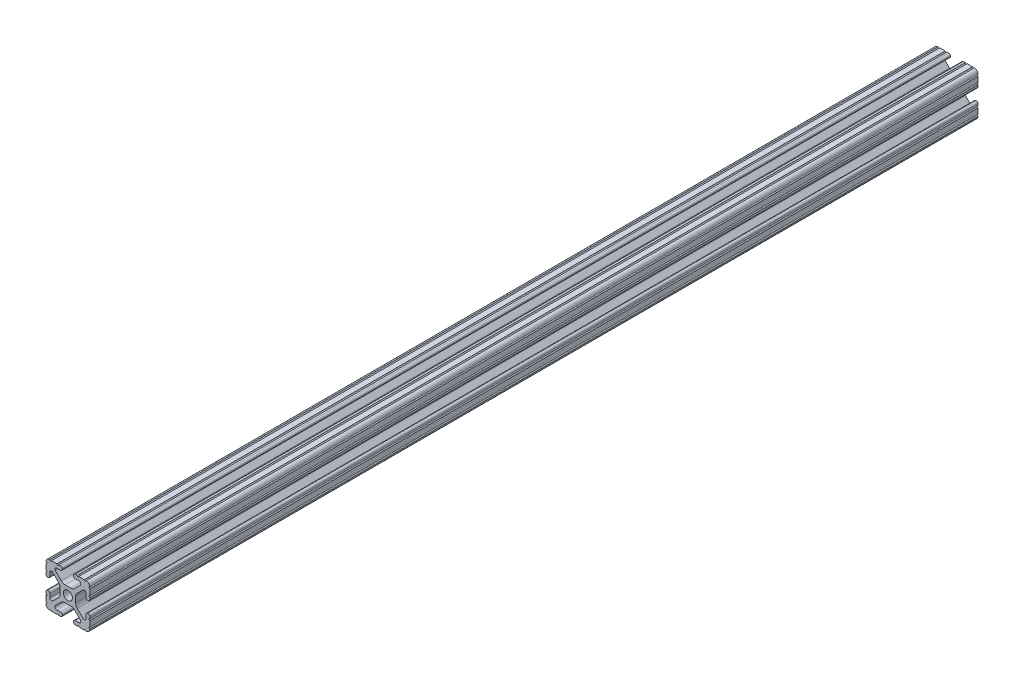
SolidWorks part; units mm, degrees
ref_plane "Front Plane" through (0, 0, 0) normal (0, 0, 1) x (1, 0, 0)
ref_plane "Top Plane" through (0, 0, 0) normal (0, 1, 0) x (1, 0, 0)
ref_plane "Right Plane" through (0, 0, 0) normal (1, 0, 0) x (0, 0, -1)
sketch "Sketch1" plane through (0, 0, 0) normal (0, 0, 1) x (1, 0, 0)
  line L88 (-7.1797, -8.6452) -> (-3.9523, -5.4237)
  line L89 (-1.7093, -4.4958) -> (1.7093, -4.4958)
  line L90 (3.9523, -5.4237) -> (7.1797, -8.6452)
  line L91 (6.4164, -10.4902) -> (4.2875, -10.4902)
  line L92 (3.2385, -11.5392) -> (3.2385, -11.651)
  line L93 (4.2875, -12.7) -> (5.3171, -12.7)
  line L94 (6.3331, -12.7) -> (9.5504, -12.7)
  line L95 (12.7, -9.5504) -> (12.7, -6.3331)
  line L96 (12.7, -5.3171) -> (12.7, -4.2875)
  line L97 (11.651, -3.2385) -> (11.5392, -3.2385)
  line L98 (10.4902, -4.2875) -> (10.4902, -6.4021)
  line L99 (8.7371, -7.1294) -> (5.441, -3.8408)
  line L100 (4.5085, -1.5932) -> (4.5085, 1.5932)
  line L101 (5.441, 3.8408) -> (8.7371, 7.1294)
  line L102 (10.4902, 6.4021) -> (10.4902, 4.2875)
  line L103 (11.5392, 3.2385) -> (11.651, 3.2385)
  line L104 (12.7, 4.2875) -> (12.7, 5.3171)
  line L105 (12.7, 6.3331) -> (12.7, 9.5504)
  line L106 (9.5504, 12.7) -> (6.3331, 12.7)
  line L107 (5.3171, 12.7) -> (4.2875, 12.7)
  line L108 (3.2385, 11.651) -> (3.2385, 11.5392)
  line L109 (4.2875, 10.4902) -> (6.4768, 10.4902)
  line L110 (7.207, 8.7244) -> (3.8983, 5.4232)
  line L111 (1.6558, 4.4958) -> (-1.6558, 4.4958)
  line L112 (-3.8983, 5.4232) -> (-7.207, 8.7244)
  line L113 (-6.4768, 10.4902) -> (-4.2875, 10.4902)
  line L114 (-3.2385, 11.5392) -> (-3.2385, 11.651)
  line L115 (-4.2875, 12.7) -> (-5.3171, 12.7)
  line L116 (-6.3331, 12.7) -> (-9.5504, 12.7)
  line L117 (-12.7, 9.5504) -> (-12.7, 6.3331)
  line L118 (-12.7, 5.3171) -> (-12.7, 4.2875)
  line L119 (-11.651, 3.2385) -> (-11.5392, 3.2385)
  line L120 (-10.4902, 4.2875) -> (-10.4902, 6.4021)
  line L121 (-8.7371, 7.1294) -> (-5.441, 3.8408)
  line L122 (-4.5085, 1.5932) -> (-4.5085, -1.5932)
  line L123 (-5.441, -3.8408) -> (-8.7371, -7.1294)
  line L124 (-10.4902, -6.4021) -> (-10.4902, -4.2875)
  line L125 (-11.5392, -3.2385) -> (-11.651, -3.2385)
  line L126 (-12.7, -4.2875) -> (-12.7, -5.3171)
  line L127 (-12.7, -6.3331) -> (-12.7, -9.5504)
  line L128 (-9.5504, -12.7) -> (-6.3331, -12.7)
  line L129 (-5.3171, -12.7) -> (-4.2875, -12.7)
  line L130 (-3.2385, -11.651) -> (-3.2385, -11.5392)
  line L131 (-4.2875, -10.4902) -> (-6.4164, -10.4902)
  circle A1 centre (0, 0) radius 2.6035
  arc A104 (-7.1797, -8.6452) -> (-6.4164, -10.4902) centre (-6.4164, -9.4098) ccw
  arc A105 (-1.7093, -4.4958) -> (-3.9523, -5.4237) centre (-1.7093, -7.6708) ccw
  arc A106 (3.9523, -5.4237) -> (1.7093, -4.4958) centre (1.7093, -7.6708) ccw
  arc A107 (6.4164, -10.4902) -> (7.1797, -8.6452) centre (6.4164, -9.4098) ccw
  arc A108 (4.2875, -10.4902) -> (3.2385, -11.5392) centre (4.2875, -11.5392) ccw
  arc A109 (3.2385, -11.651) -> (4.2875, -12.7) centre (4.2875, -11.651) ccw
  arc A110 (6.3331, -12.7) -> (5.3171, -12.7) centre (5.8251, -12.7) ccw
  arc A111 (10.5664, -12.6998) -> (9.5504, -12.7) centre (10.0584, -12.7) ccw
  arc A112 (10.5664, -12.6998) -> (12.6998, -10.5664) centre (10.5918, -10.5918) ccw
  arc A113 (12.7, -9.5504) -> (12.6998, -10.5664) centre (12.7, -10.0584) ccw
  arc A114 (12.7, -5.3171) -> (12.7, -6.3331) centre (12.7, -5.8251) ccw
  arc A115 (12.7, -4.2875) -> (11.651, -3.2385) centre (11.651, -4.2875) ccw
  arc A116 (11.5392, -3.2385) -> (10.4902, -4.2875) centre (11.5392, -4.2875) ccw
  arc A117 (8.7371, -7.1294) -> (10.4902, -6.4021) centre (9.4628, -6.4021) ccw
  arc A118 (4.5085, -1.5932) -> (5.441, -3.8408) centre (7.6835, -1.5932) ccw
  arc A119 (5.441, 3.8408) -> (4.5085, 1.5932) centre (7.6835, 1.5932) ccw
  arc A120 (10.4902, 6.4021) -> (8.7371, 7.1294) centre (9.4628, 6.4021) ccw
  arc A121 (10.4902, 4.2875) -> (11.5392, 3.2385) centre (11.5392, 4.2875) ccw
  arc A122 (11.651, 3.2385) -> (12.7, 4.2875) centre (11.651, 4.2875) ccw
  arc A123 (12.7, 6.3331) -> (12.7, 5.3171) centre (12.7, 5.8251) ccw
  arc A124 (12.6998, 10.5664) -> (12.7, 9.5504) centre (12.7, 10.0584) ccw
  arc A125 (12.6998, 10.5664) -> (10.5664, 12.6998) centre (10.5918, 10.5918) ccw
  arc A126 (9.5504, 12.7) -> (10.5664, 12.6998) centre (10.0584, 12.7) ccw
  arc A127 (5.3171, 12.7) -> (6.3331, 12.7) centre (5.8251, 12.7) ccw
  arc A128 (4.2875, 12.7) -> (3.2385, 11.651) centre (4.2875, 11.651) ccw
  arc A129 (3.2385, 11.5392) -> (4.2875, 10.4902) centre (4.2875, 11.5392) ccw
  arc A130 (7.207, 8.7244) -> (6.4768, 10.4902) centre (6.4768, 9.4563) ccw
  arc A131 (1.6558, 4.4958) -> (3.8983, 5.4232) centre (1.6558, 7.6708) ccw
  arc A132 (-3.8983, 5.4232) -> (-1.6558, 4.4958) centre (-1.6558, 7.6708) ccw
  arc A133 (-6.4768, 10.4902) -> (-7.207, 8.7244) centre (-6.4768, 9.4563) ccw
  arc A134 (-4.2875, 10.4902) -> (-3.2385, 11.5392) centre (-4.2875, 11.5392) ccw
  arc A135 (-3.2385, 11.651) -> (-4.2875, 12.7) centre (-4.2875, 11.651) ccw
  arc A136 (-6.3331, 12.7) -> (-5.3171, 12.7) centre (-5.8251, 12.7) ccw
  arc A137 (-10.5664, 12.6998) -> (-9.5504, 12.7) centre (-10.0584, 12.7) ccw
  arc A138 (-10.5664, 12.6998) -> (-12.6998, 10.5664) centre (-10.5918, 10.5918) ccw
  arc A139 (-12.7, 9.5504) -> (-12.6998, 10.5664) centre (-12.7, 10.0584) ccw
  arc A140 (-12.7, 5.3171) -> (-12.7, 6.3331) centre (-12.7, 5.8251) ccw
  arc A141 (-12.7, 4.2875) -> (-11.651, 3.2385) centre (-11.651, 4.2875) ccw
  arc A142 (-11.5392, 3.2385) -> (-10.4902, 4.2875) centre (-11.5392, 4.2875) ccw
  arc A143 (-8.7371, 7.1294) -> (-10.4902, 6.4021) centre (-9.4628, 6.4021) ccw
  arc A144 (-4.5085, 1.5932) -> (-5.441, 3.8408) centre (-7.6835, 1.5932) ccw
  arc A145 (-5.441, -3.8408) -> (-4.5085, -1.5932) centre (-7.6835, -1.5932) ccw
  arc A146 (-10.4902, -6.4021) -> (-8.7371, -7.1294) centre (-9.4628, -6.4021) ccw
  arc A147 (-10.4902, -4.2875) -> (-11.5392, -3.2385) centre (-11.5392, -4.2875) ccw
  arc A148 (-11.651, -3.2385) -> (-12.7, -4.2875) centre (-11.651, -4.2875) ccw
  arc A149 (-12.7, -6.3331) -> (-12.7, -5.3171) centre (-12.7, -5.8251) ccw
  arc A150 (-12.6998, -10.5664) -> (-12.7, -9.5504) centre (-12.7, -10.0584) ccw
  arc A151 (-12.6998, -10.5664) -> (-10.5664, -12.6998) centre (-10.5918, -10.5918) ccw
  arc A152 (-9.5504, -12.7) -> (-10.5664, -12.6998) centre (-10.0584, -12.7) ccw
  arc A153 (-5.3171, -12.7) -> (-6.3331, -12.7) centre (-5.8251, -12.7) ccw
  arc A154 (-4.2875, -12.7) -> (-3.2385, -11.651) centre (-4.2875, -11.651) ccw
  arc A155 (-3.2385, -11.5392) -> (-4.2875, -10.4902) centre (-4.2875, -11.5392) ccw
extrude "Boss-Extrude1" add sketch "Sketch1" along normal mid plane 609.6
sketch "Sketch2" plane through (0, 0, 304.8) normal (0, 0, 1) x (1, 0, 0)
  line L1 (-15.377, 16.343) -> (15.7647, 16.343)
  line L2 (-15.377, 16.343) -> (-15.377, -15.0292)
  line L3 (-15.377, -15.0292) -> (15.7647, -15.0292)
  line L4 (15.7647, 16.343) -> (15.7647, -15.0292)
extrude "Cut-Extrude1" cut sketch "Sketch2" against normal blind 94.234
